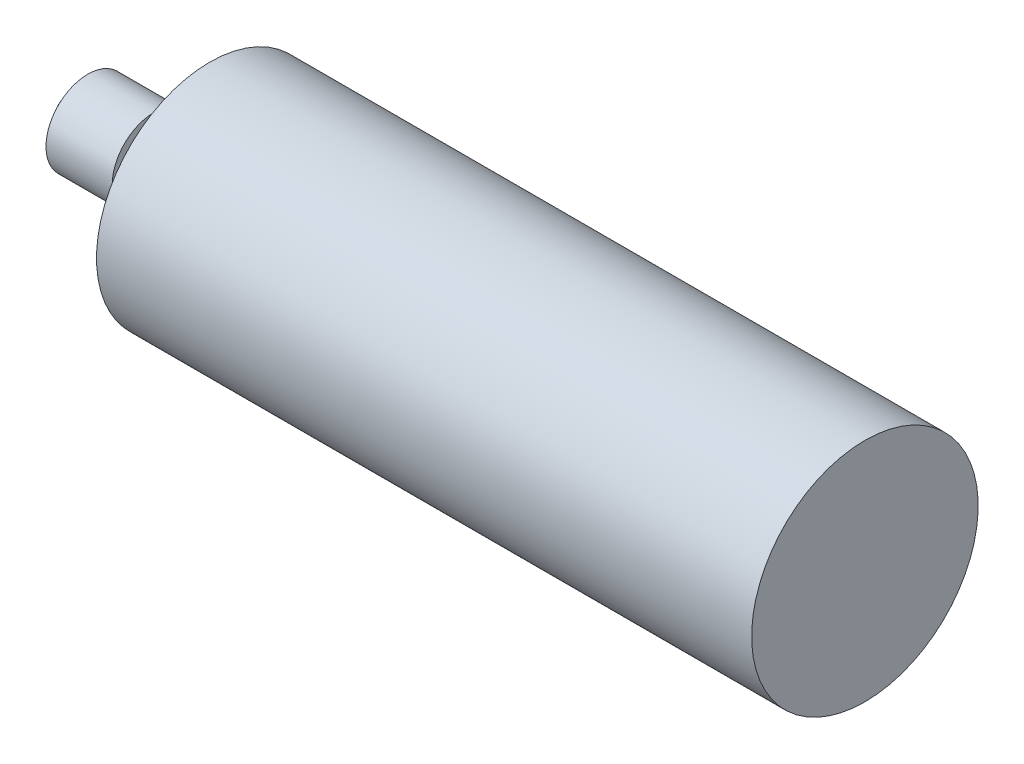
SolidWorks part; units mm, degrees
ref_plane "前视基准面" through (0, 0, 0) normal (0, 0, 1) x (1, 0, 0)
ref_plane "上视基准面" through (0, 0, 0) normal (0, 1, 0) x (1, 0, 0)
ref_plane "右视基准面" through (0, 0, 0) normal (1, 0, 0) x (0, 0, -1)
other "Configuration Table"
sketch "草图1" plane through (0, 0, 0) normal (0, 0, 1) x (1, 0, 0)
  line L0 (0, 0) -> (0, 12)
  line L1 (0, 12) -> (19, 12)
  line L6 (35, 24) -> (35, 32.5)
  line L7 (35, 32.5) -> (223, 32.5)
  line L8 (223, 32.5) -> (223, 0)
  line L9 (223, 0) -> (0, 0)
  line L10 (19, 12) -> (19, 9)
  line L11 (19, 9) -> (33, 9)
  line L12 (33, 9) -> (33, 24)
  line L13 (33, 24) -> (35, 24)
  dimension "D1" = 188
  dimension "D2" = 32.5
  dimension "D3" = 35
  dimension "D4" = 2
  dimension "D5" = 14
  dimension "D6" = 12
  dimension "D7" = 15
  dimension "D8" = 3
revolve "旋转1" add sketch "草图1" angle 360 about L9
sketch "草图2" plane through (0, 0, 0) normal (-1, 0, 0) x (0, 0, 1)
  circle A0 centre (0, 0) radius 5
  dimension "D1" = 10
extrude "凸台-拉伸2" add sketch "草图2" along normal blind 5
